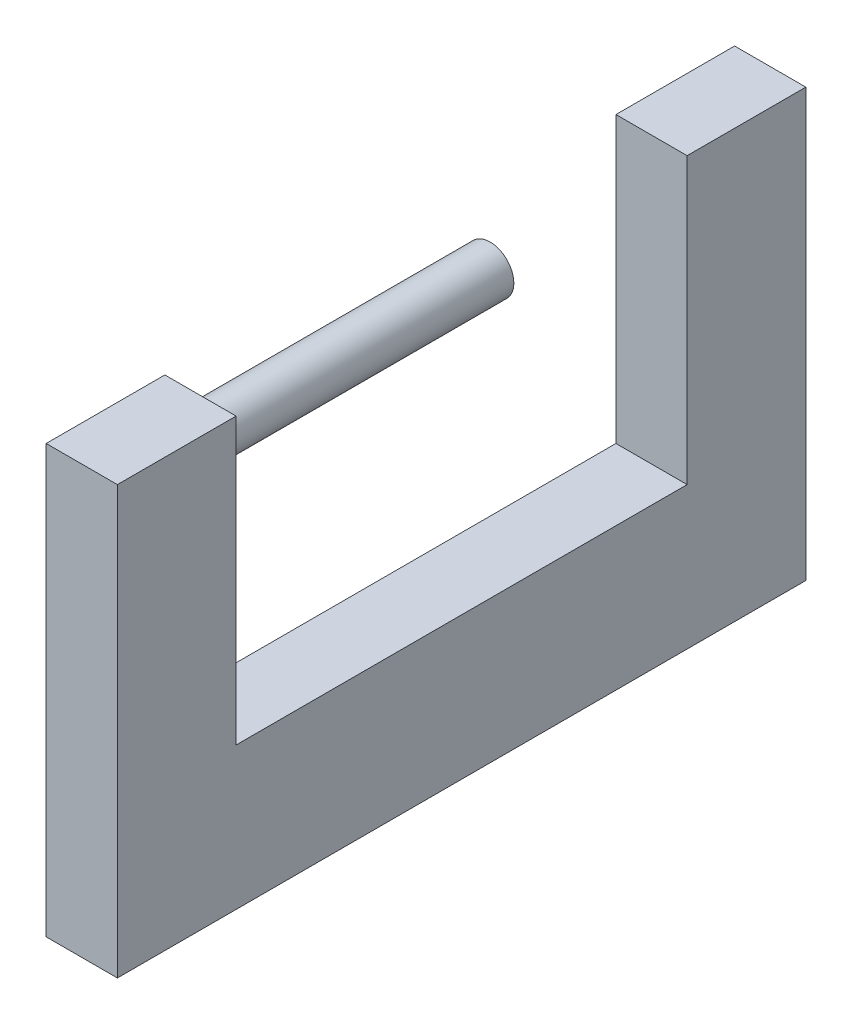
SolidWorks part; units mm, degrees
ref_plane "Front Plane" through (0, 0, 0) normal (1, 0, 0) x (0, 1, 0)
ref_plane "Top Plane" through (0, 0, 0) normal (0, 0, 1) x (0, 1, 0)
ref_plane "Right Plane" through (0, 0, 0) normal (0, 1, 0) x (-1, 0, 0)
sketch "Sketch1" plane through (0, 0, 0) normal (1, 0, 0) x (0, 1, 0)
  line L0 (0, 0) -> (0, 95)
  line L1 (0, 95) -> (60, 95)
  line L2 (60, 95) -> (60, 120)
  line L3 (60, 120) -> (-30, 120)
  line L4 (-30, 120) -> (-30, -25)
  line L5 (-30, -25) -> (60, -25)
  line L6 (60, -25) -> (60, 0)
  line L7 (60, 0) -> (0, 0)
  point P3 (64.6955, 0)
  dimension "D1" = 30
  dimension "D2" = 25
  dimension "D3" = 25
  dimension "D4" = 90
  dimension "D5" = 145
extrude "Boss-Extrude1" add sketch "Sketch1" along normal blind 15
sketch "Sketch2" plane through (0, 0, 95) normal (0, 0, -1) x (1, 0, 0)
  line L0 (15, -60) -> (0, -60) construction
  circle A0 centre (7.5, -52.5) radius 5
  point P4 (7.5, -60)
  dimension "D1" = 10
  dimension "D2" = 7.5
extrude "Boss-Extrude2" add sketch "Sketch2" along normal blind 61
